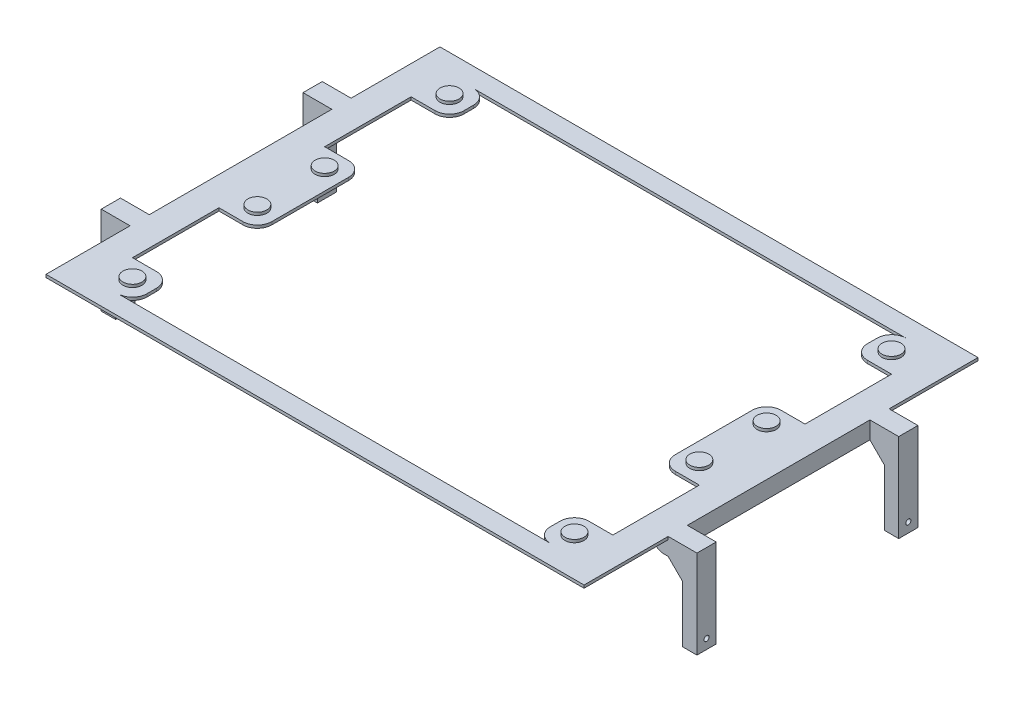
SolidWorks part; units mm, degrees
ref_plane "Front Plane" through (0, 0, 0) normal (0, 0, 1) x (1, 0, 0)
ref_plane "Top Plane" through (0, 0, 0) normal (0, 1, 0) x (1, 0, 0)
ref_plane "Right Plane" through (0, 0, 0) normal (1, 0, 0) x (0, 0, -1)
sketch "Sketch1" plane through (0, 0, 0) normal (0, 1, 0) x (1, 0, 0)
  line L0 (0, 185) -> (500, 185)
  line L1 (0, 0) -> (500, 0)
  line L2 (0, 0) -> (0, 370)
  line L3 (0, 370) -> (500, 370)
  line L4 (500, 0) -> (500, 370)
  line L5 (40, 15) -> (40, 25)
  line L6 (25, 330) -> (-30, 330)
  line L7 (40, 345) -> (40, 355)
  line L8 (25, 370) -> (-30, 370)
  line L9 (-30, 330) -> (-30, 370)
  line L10 (25, 0) -> (-30, 0)
  line L11 (-30, 0) -> (-30, 40)
  line L12 (25, 40) -> (-30, 40)
  line L13 (250, 370) -> (250, 0)
  line L14 (25, 130) -> (-30, 130)
  line L15 (40, 145) -> (40, 225)
  line L16 (25, 240) -> (-30, 240)
  line L17 (-30, 130) -> (-30, 240)
  line L18 (-30, 330) -> (0, 330)
  line L19 (-30, 330) -> (-30, 0)
  line L20 (-30, 0) -> (0, 0)
  line L21 (0, 330) -> (0, 0)
  line L22 (475, 0) -> (530, 0)
  line L23 (530, 0) -> (530, 40)
  line L24 (475, 40) -> (530, 40)
  line L25 (460, 15) -> (460, 25)
  line L26 (475, 240) -> (530, 240)
  line L27 (530, 130) -> (530, 240)
  line L28 (475, 130) -> (530, 130)
  line L29 (460, 145) -> (460, 225)
  line L30 (530, 0) -> (500, 0)
  line L31 (500, 330) -> (500, 0)
  line L32 (530, 330) -> (500, 330)
  line L33 (530, 330) -> (530, 0)
  line L34 (475, 370) -> (530, 370)
  line L35 (530, 330) -> (530, 370)
  line L36 (475, 330) -> (530, 330)
  line L37 (460, 345) -> (460, 355)
  line L38 (530, 0) -> (500, 0)
  line L39 (500, 330) -> (500, 0)
  line L40 (530, 330) -> (500, 330)
  line L41 (530, 330) -> (530, 0)
  line L43 (530, 330) -> (500, 330)
  line L44 (530, 330) -> (530, 40)
  line L45 (530, 40) -> (500, 40)
  line L46 (500, 330) -> (500, 40)
  line L47 (-30, 370) -> (530, 370)
  line L48 (-30, 370) -> (-30, 390)
  line L49 (-30, 390) -> (530, 390)
  line L50 (530, 370) -> (530, 390)
  line L51 (-30, 0) -> (530, 0)
  line L52 (-30, 0) -> (-30, -20)
  line L53 (-30, -20) -> (530, -20)
  line L54 (530, 0) -> (530, -20)
  circle A4 centre (20, 350) radius 10
  circle A5 centre (20, 220) radius 10
  circle A8 centre (480, 350) radius 10
  circle A9 centre (480, 220) radius 10
  circle A10 centre (480, 150) radius 10
  circle A11 centre (480, 20) radius 10
  circle A12 centre (20, 150) radius 10
  circle A13 centre (20, 20) radius 10
  arc A14 (40, 355) -> (25, 370) centre (25, 355) ccw
  arc A15 (25, 330) -> (40, 345) centre (25, 345) ccw
  arc A16 (25, 0) -> (40, 15) centre (25, 15) ccw
  arc A17 (40, 25) -> (25, 40) centre (25, 25) ccw
  arc A18 (25, 130) -> (40, 145) centre (25, 145) ccw
  arc A19 (40, 225) -> (25, 240) centre (25, 225) ccw
  circle A20 centre (480, 20) radius 10
  arc A21 (475, 0) -> (460, 15) centre (475, 15) cw
  arc A22 (460, 25) -> (475, 40) centre (475, 25) cw
  circle A23 centre (480, 150) radius 10
  circle A24 centre (480, 220) radius 10
  arc A25 (475, 130) -> (460, 145) centre (475, 145) cw
  arc A26 (460, 225) -> (475, 240) centre (475, 225) cw
  circle A27 centre (480, 350) radius 10
  arc A28 (460, 355) -> (475, 370) centre (475, 355) cw
  arc A29 (475, 330) -> (460, 345) centre (475, 345) cw
  point P31 (40, 330)
  point P90 (0, 0)
  dimension "D3" = 20
  dimension "D4" = 20
  dimension "D5" = 20
  dimension "D10" = 35
  dimension "D15" = 15
  dimension "D22" = 15
  dimension "D1" = 500
  dimension "D2" = 370
  dimension "D6" = 35
  dimension "D7" = 20
  dimension "D8" = 2
  dimension "D11" = 20
  dimension "D12" = 20
  dimension "D13" = 20
  dimension "D14" = 70
  dimension "D17" = 20
  dimension "D18" = 20
  dimension "D19" = 20
  dimension "D20" = 20
  dimension "D21" = 0
  dimension "D23" = 0
  dimension "D24" = 0
  dimension "D25" = 0
  dimension "D26" = 0
  dimension "D27" = 20
  dimension "D28" = 20
  dimension "D29" = 0
  dimension "D30" = 560
  dimension "D31" = 0
  dimension "D9" = 2
  dimension "D16" = 2
extrude "Boss-Extrude1" add sketch "Sketch1" along normal blind 3 contours L2 L12 L11 L10 | L54 L22 L1 L10 L52 L53 | L5 A17 L12 L2 L1 A16 A13 | A13 | L14 A18 L15 L0 L2 A12 | L15 A19 L16 L2 L0 A5 | A12 | L17 L14 L2 L16 | A5 | L9 L6 L2 L8 | L6 L19 L16 L2 | L14 L19 L12 L2 | A4 | L6 A15 L7 A14 L3 L2 A4 | L34 L50 L49 L48 L8 L3 | L33 L28 L4 L24 | L33 L32 L4 L26 | L32 L35 L34 L4 | A29 L36 L4 L3 A28 L37 A8 | A8 | A26 L29 L0 L4 L26 A9 | L4 L28 L27 L26 | A25 L28 L4 L0 L29 A10 | A10 | A9
sketch "Sketch2" plane through (0, 3, 0) normal (0, 1, 0) x (1, 0, 0)
  circle A0 centre (20, 150) radius 9.9
  circle A1 centre (20, 220) radius 9.9
  circle A2 centre (20, 350) radius 9.9
  circle A3 centre (20, 20) radius 9.9
  circle A4 centre (480, 150) radius 9.9
  circle A5 centre (480, 220) radius 9.9
  circle A6 centre (480, 350) radius 9.9
  circle A7 centre (480, 20) radius 9.9
  dimension "D1" = 19.8
extrude "Boss-Extrude2" add sketch "Sketch2" along normal blind 3
sketch "Sketch3" plane through (0, 3, 0) normal (0, 1, 0) x (1, 0, 0)
  line L0 (560, 287.5) -> (-60, 287.5)
  line L1 (-60, 277.5) -> (-40, 277.5)
  line L2 (-60, 277.5) -> (-60, 297.5)
  line L3 (-60, 297.5) -> (-40, 297.5)
  line L4 (-40, 277.5) -> (-40, 297.5)
  line L5 (540, 277.5) -> (560, 277.5)
  line L6 (540, 277.5) -> (540, 297.5)
  line L7 (540, 297.5) -> (560, 297.5)
  line L8 (560, 277.5) -> (560, 297.5)
  line L9 (-30, 390) -> (530, 390) construction
  line L12 (-30, -20) -> (-30, 390) construction
  line L13 (-40, 297.5) -> (-30, 297.5)
  line L14 (-40, 297.5) -> (-40, 277.5)
  line L15 (-40, 277.5) -> (-30, 277.5)
  line L16 (-30, 297.5) -> (-30, 277.5)
  line L17 (530, 390) -> (530, -20) construction
  line L18 (540, 297.5) -> (530, 297.5)
  line L19 (540, 297.5) -> (540, 277.5)
  line L20 (540, 277.5) -> (530, 277.5)
  line L21 (530, 297.5) -> (530, 277.5)
  point P12 (250, 390)
  point P13 (250, 287.5)
  line M17 (530, -20) -> (530, 390)
  line M19 (-30, 390) -> (-30, -20)
  dimension "D1" = 620
  dimension "D2" = 0
  dimension "D3" = 20
  dimension "D4" = 20
  dimension "D5" = 102.5
  dimension "D6" = 20
  dimension "D7" = 20
extrude "Boss-Extrude3" add sketch "Sketch3" against normal blind 92 contours L4 L15 L0 M19 | L1 L4 L0 L2 | L0 L4 L3 L2 | L13 L4 L0 M19 | L5 L8 L0 L6 | L0 L8 L7 L6 | L6 L18 L0 M17 | L20 L6 L0 M17
pattern_linear "LPattern1" count 2 spacing 210 along (0, 0, 1) of "Boss-Extrude3"
sketch "Sketch4" plane through (0, 0, -67.5) normal (0, 0, 1) x (1, 0, 0)
  line L0 (530, -89) -> (530, 0) construction
  line L1 (530, -15) -> (515, -15)
  line L2 (530, -15) -> (530, 0)
  line L3 (530, 0) -> (515, 0)
  line L4 (515, -15) -> (515, 0)
  line L5 (-30, 0) -> (530, 0) construction
  dimension "D1" = 15
  dimension "D2" = 15
extrude "Boss-Extrude4" add sketch "Sketch4" against normal up to surface (230 mm away) up to face at (-42, -34.4, -297.5)
fillet "Fillet1" radius 10 1 edges at (515, -15, -182.5)
ref_plane "Plane1" through (250, 0, 0) normal (1, 0, 0) x (0, 0, -1)
mirror "Mirror1" about plane through (250, 0, 0) normal (1, 0, 0) of "Fillet1", "Boss-Extrude4"
sketch "Sketch5" plane through (-30, 0, 0) normal (1, 0, 0) x (0, 0, -1)
  line L0 (67.5, -89) -> (67.5, -15) construction
  line L1 (87.5, -89) -> (67.5, -89) construction
  line L2 (297.5, -89) -> (277.5, -89) construction
  line L3 (277.5, -89) -> (277.5, -15) construction
  circle A0 centre (77.5, -79) radius 2.65
  circle A1 centre (287.5, -79) radius 2.65
  dimension "D1" = 5.3
  dimension "D4" = 5.3
  dimension "D2" = 10
  dimension "D3" = 10
  dimension "D5" = 10
  dimension "D6" = 10
extrude "Cut-Extrude1" cut sketch "Sketch5" against normal blind 92
mirror "Mirror2" about plane through (250, 0, 0) normal (1, 0, 0) of "Cut-Extrude1"
sketch "Sketch6" plane through (0, 0, -67.5) normal (0, 0, 1) x (1, 0, 0)
  line L0 (-45, -89) -> (-45, -30)
  line L1 (-60, -89) -> (-30, -89) construction
  line L2 (-45, -30) -> (-30, -15)
  line L3 (-30, -15) -> (-30, -89)
  line L4 (-30, -89) -> (-45, -89)
  dimension "D1" = 135
extrude "Cut-Extrude2" cut sketch "Sketch6" against normal through all
mirror "Mirror3" about plane through (250, 0, 0) normal (1, 0, 0) of "Cut-Extrude2"
